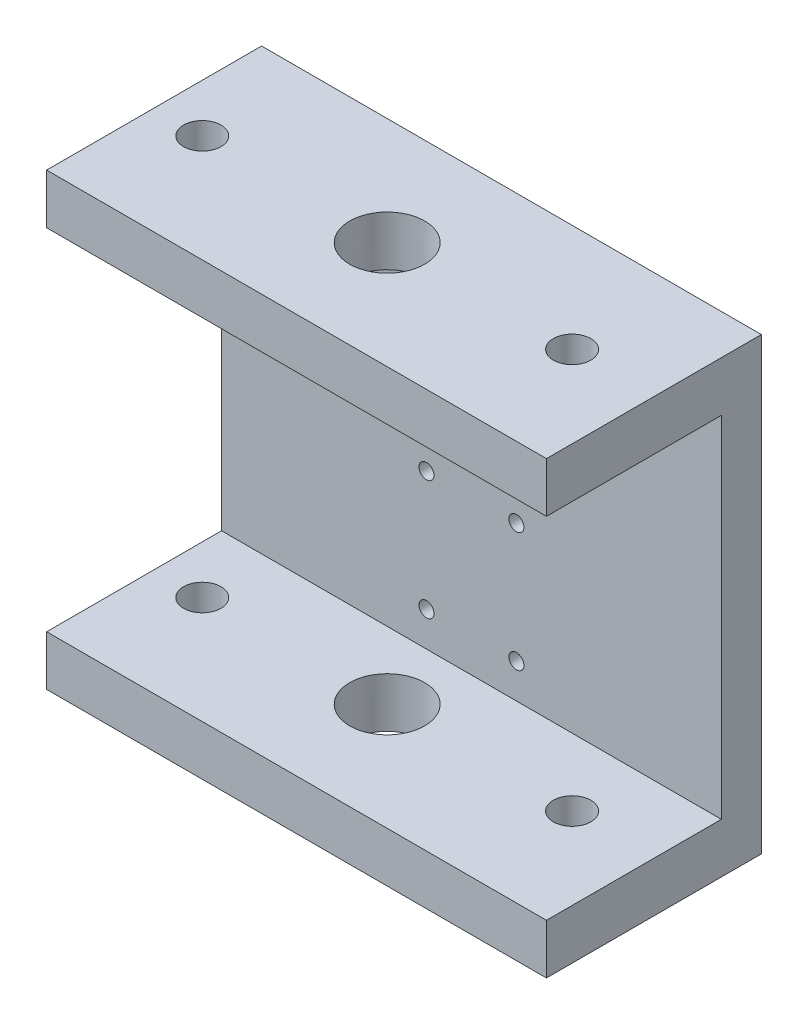
SolidWorks part; units mm, degrees
ref_plane "Front Plane" through (0, 0, 0) normal (0, 0, 1) x (1, 0, 0)
ref_plane "Top Plane" through (0, 0, 0) normal (0, 1, 0) x (1, 0, 0)
ref_plane "Right Plane" through (0, 0, 0) normal (1, 0, 0) x (0, 0, -1)
sketch "Sketch2" plane through (0, 0, 0) normal (0, 0, 1) x (1, 0, 0)
  line L0 (-9, 28.0946) -> (9, 4.1659) construction
  line L5 (9, -4.1659) -> (-9, -28.0946) construction
  line L6 (-50, 45) -> (50, 45)
  line L7 (-50, 45) -> (-50, -45)
  line L8 (-50, -45) -> (50, -45)
  line L9 (50, 45) -> (50, -45)
  line L10 (-9, -4.1659) -> (9, -28.0946) construction
  line L11 (-9, 4.1659) -> (9, 28.0946) construction
  circle A7 centre (-9, -4.1659) radius 1.5
  circle A12 centre (9, -28.0946) radius 1.5
  circle A13 centre (9, -4.1659) radius 1.5
  circle A18 centre (-9, -28.0946) radius 1.5
  circle A23 centre (-9, 28.0946) radius 1.5
  circle A24 centre (9, 28.0946) radius 1.5
  circle A25 centre (9, 4.1659) radius 1.5
  circle A26 centre (-9, 4.1659) radius 1.5
  point P0 (0, 16.1303)
  point P1 (0, -16.1303)
  point P5 (0, 0)
  dimension "D1" = 32.2605
extrude "Boss-Extrude1" add sketch "Sketch2" along normal blind 8
sketch "Sketch5" plane through (0, 0, 8) normal (0, 0, 1) x (1, 0, 0)
  line L8 (-50, 35) -> (-50, 45)
  line L10 (-50, 45) -> (50, 45)
  line L13 (50, -45) -> (50, 45) construction
  line L14 (50, 35) -> (-50, 35)
  line L19 (50, 45) -> (50, 35)
  line L22 (-50, 45) -> (-50, -45) construction
  line L24 (-50, -35) -> (-50, -45)
  line L25 (50, -35) -> (-50, -35)
  line L26 (50, -45) -> (50, -35)
  line L29 (-50, -45) -> (50, -45)
extrude "Boss-Extrude2" add sketch "Sketch5" along normal blind 35
sketch "Sketch7" plane through (0, 45, 0) normal (0, 1, 0) x (1, 0, 0)
  circle A0 centre (-3.365, -21.5) radius 7.5
  circle A1 centre (-40.365, -21.5) radius 3.75
  circle A2 centre (33.635, -21.5) radius 3.75
  dimension "D1" = 15
  dimension "D4" = 7.5
  dimension "D5" = 7.5
extrude "Cut-Extrude2" cut sketch "Sketch7" against normal blind 290
